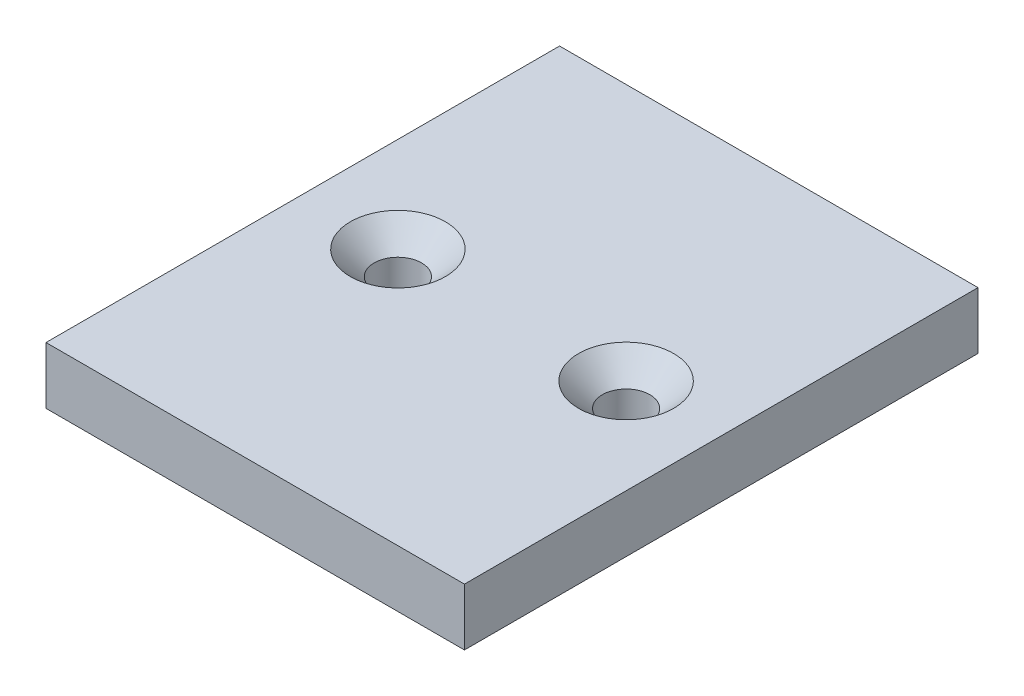
SolidWorks part; units mm, degrees
ref_plane "Front Plane" through (0, 0, 0) normal (0, 0, 1) x (1, 0, 0)
ref_plane "Top Plane" through (0, 0, 0) normal (0, 1, 0) x (1, 0, 0)
ref_plane "Right Plane" through (0, 0, 0) normal (1, 0, 0) x (0, 0, -1)
sketch "Sketch1" plane through (0, 0, 0) normal (0, 0, 1) x (1, 0, 0)
  line L1 (0, 0) -> (44, 0)
  line L2 (0, 0) -> (0, 6)
  line L3 (0, 6) -> (44, 6)
  line L4 (44, 0) -> (44, 6)
  dimension "D1" = 44
  dimension "D2" = 6
extrude "Extrude1" add sketch "Sketch1" along normal mid plane 54
sketch "Sketch3" plane through (0, 6, 0) normal (0, 1, 0) x (1, 0, 0)
  point P5 (10, 0)
  point P6 (34, 0)
  dimension "D1" = 24
hole_wizard "CSK for M6 Flat Head Machine Screw1" positions "3DSketch1" profile "Sketch4" countersink size "M6" standard "Ansi Metric" end condition through all
sketch3d "3DSketch1"
  point P0 (10, 6, 0)
  point P3 (34, 6, 0)
sketch "Sketch4" plane through (10, 6, 0) normal (1, 0, 0) x (0, 0, 1)
  line L0 (0, 0) -> (0, 6)
  line L1 (0, 6) -> (2.5, 6)
  line L2 (2.5, 6) -> (2.5, 2.5)
  line L3 (2.5, 2.5) -> (5, 0)
  line L5 (5, 0) -> (0, 0)
  line L6 (-2.5, 2.5) -> (-5, 0) construction
  line L11 (0, -6.35) -> (0, 107.95) construction
  dimension "Thru Hole Dia." = 5
  dimension "Thru Hole Depth" = 6
  dimension "Near C'Sink Dia." = 10
  dimension "Near C'Sink Angle" = 90
